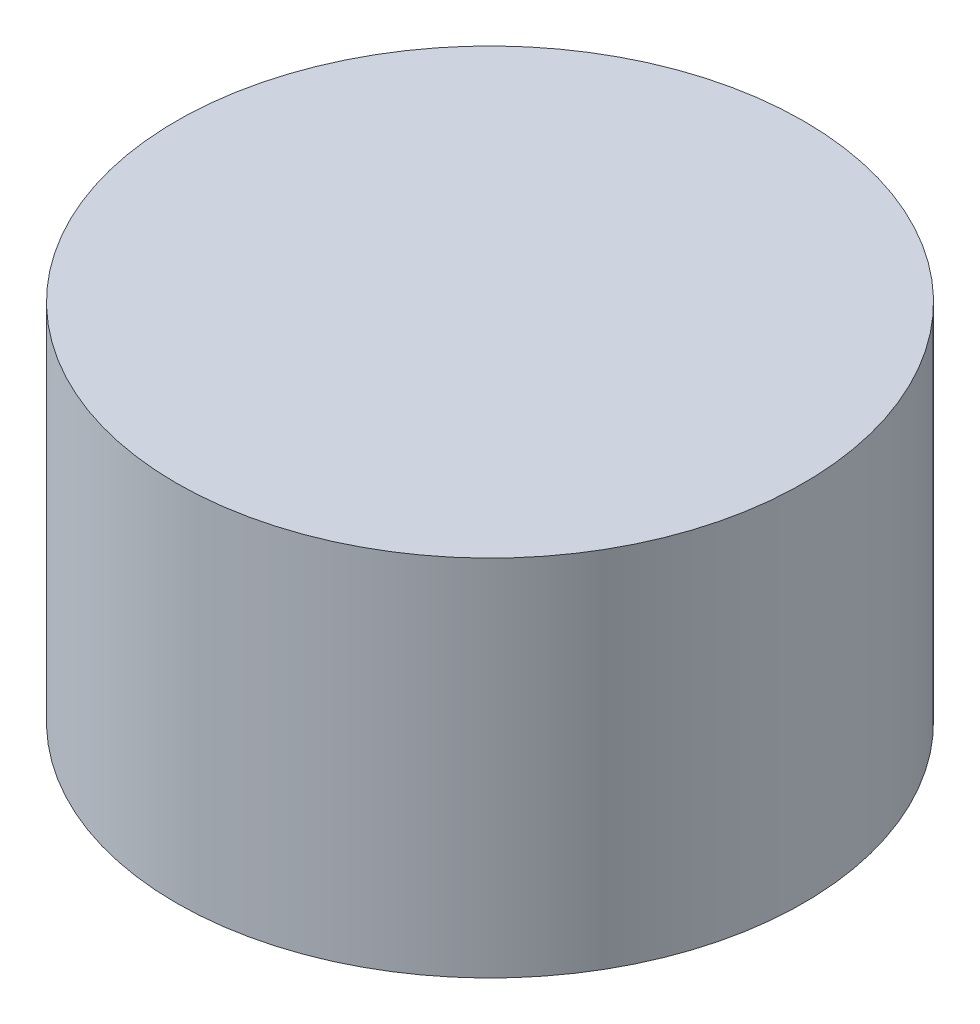
SolidWorks part; units mm, degrees
ref_plane "Front Plane" through (0, 0, 0) normal (0, 0, 1) x (1, 0, 0)
ref_plane "Top Plane" through (0, 0, 0) normal (0, 1, 0) x (1, 0, 0)
ref_plane "Right Plane" through (0, 0, 0) normal (1, 0, 0) x (0, 0, -1)
sketch "Sketch1" plane through (0, 0, 0) normal (0, 1, 0) x (1, 0, 0)
  circle A0 centre (0, 0) radius 1.725
  dimension "D1" = 3.45
extrude "Boss-Extrude1" add sketch "Sketch1" along normal blind 2
